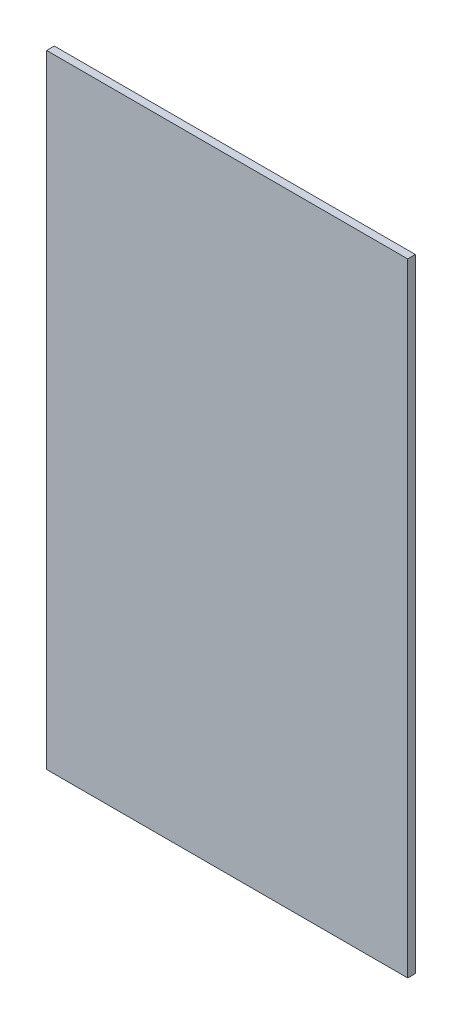
SolidWorks part; units mm, degrees
ref_plane "Front Plane" through (0, 0, 0) normal (0, 0, 1) x (1, 0, 0)
ref_plane "Top Plane" through (0, 0, 0) normal (0, 1, 0) x (1, 0, 0)
ref_plane "Right Plane" through (0, 0, 0) normal (1, 0, 0) x (0, 0, -1)
sketch "Sketch1" plane through (0, 0, 0) normal (0, 0, 1) x (1, 0, 0)
  line L1 (0, 0) -> (141.39, 0)
  line L2 (0, 0) -> (0, 243.83)
  line L3 (0, 243.83) -> (141.39, 243.83)
  line L4 (141.39, 0) -> (141.39, 243.83)
  dimension "D1" = 141.39
  dimension "D2" = 243.83
extrude "Boss-Extrude1" add sketch "Sketch1" along normal blind 3
